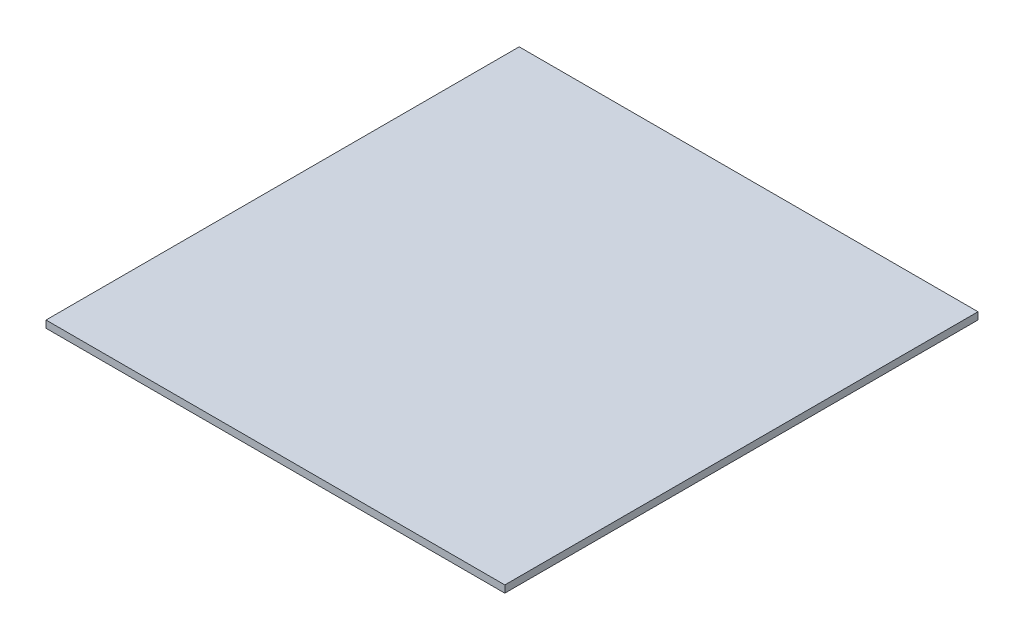
SolidWorks part; units mm, degrees
ref_plane "Front Plane" through (0, 0, 0) normal (0, 0, 1) x (1, 0, 0)
ref_plane "Top Plane" through (0, 0, 0) normal (0, 1, 0) x (1, 0, 0)
ref_plane "Right Plane" through (0, 0, 0) normal (1, 0, 0) x (0, 0, -1)
sketch "Sketch1" plane through (0, 0, 0) normal (0, 1, 0) x (1, 0, 0)
  line L0 (147, 135) -> (-173, 135)
  line L1 (147, 135) -> (147, -195)
  line L2 (147, -195) -> (-173, -195)
  line L3 (-173, -195) -> (-173, 135)
extrude "Boss-Extrude1" add sketch "Sketch1" along normal blind 5
